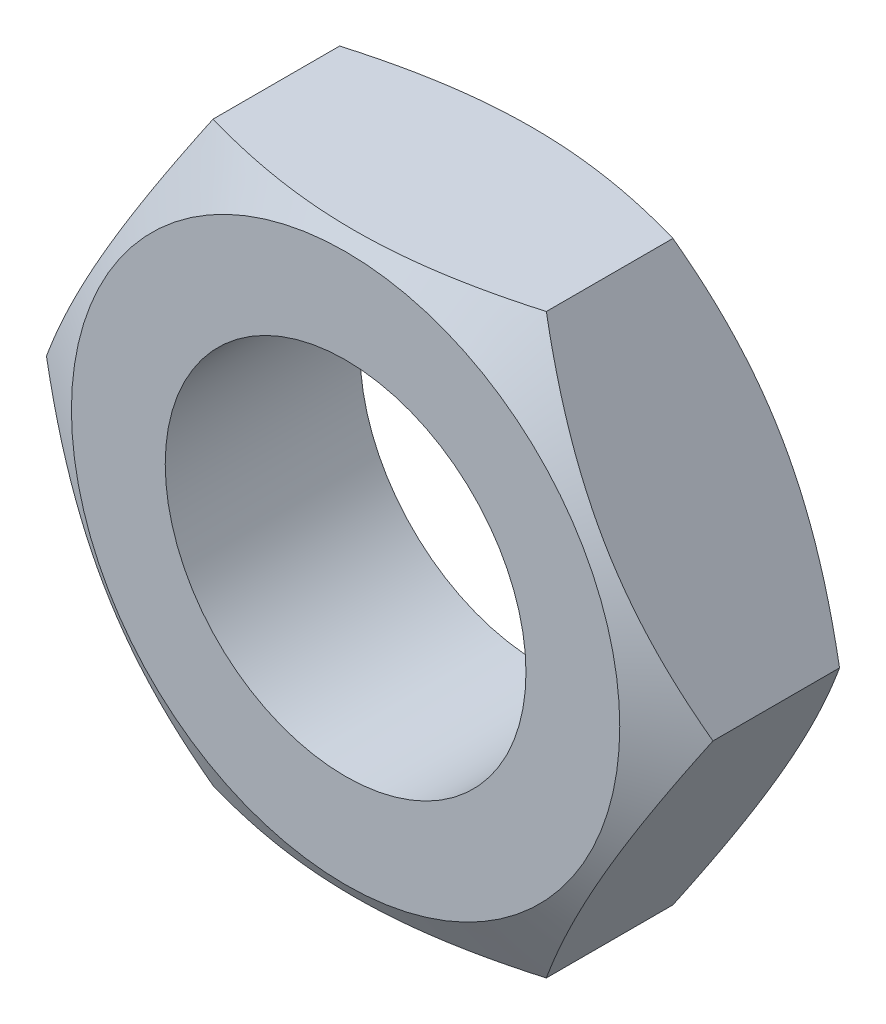
SolidWorks part; units mm, degrees
ref_plane "Plane1" through (0, 0, 0) normal (0, 0, 1) x (1, 0, 0)
ref_plane "Plane2" through (0, 0, 0) normal (0, 1, 0) x (1, 0, 0)
ref_plane "Plane3" through (0, 0, 0) normal (1, 0, 0) x (0, 0, -1)
sketch "BaseNutSke" plane through (0, 0, 0) normal (0, 0, 1) x (1, 0, 0)
  line L6 (2.3094, -4) -> (-2.3094, -4)
  line L7 (2.3094, 4) -> (-2.3094, 4)
  line L8 (2.3094, -4) -> (4.6188, 0)
  line L9 (4.6188, 0) -> (2.3094, 4)
  line L10 (-2.3094, 4) -> (-4.6188, 0)
  line L11 (-4.6188, 0) -> (-2.3094, -4)
  circle A0 centre (0, 0) radius 2.1 construction
  circle A1 centre (0, 0) radius 4.6188 construction
  circle A2 centre (0, 0) radius 2.5
  dimension "Tap_drill" = 4.2
  dimension "Diameter" = 5
  dimension "Width_flats" = 8
extrude "BaseNut" add sketch "BaseNutSke" against normal blind 2.7
cosmetic thread "ThreadCosmetic" [suppressed] parameters "Thread_major"=5
ref_plane "Plane4" through (0, 0, -1.35) normal (0, 0, -1) x (-1, 0, 0)
sketch "Sketch6" plane through (0, 0, -2.7) normal (0, 0, -1) x (-1, 0, 0)
  circle A0 centre (0, 0) radius 3.8
  dimension "D1" = 7.6
extrude "Cut-Extrude2" cut sketch "Sketch6" against normal through all draft 60 flip side to cut
mirror "Mirror1" about plane through (0, 0, -1.35) normal (0, 0, -1) of "Cut-Extrude2"
equation "\"D1@Sketch3\" = \"Width_flats@BaseNutSke\" /2"
equation "' \"Num_threads@ThdSchPat\" = \"Num_threads@ThdSchPat\" - sgn( \"Num_threads@ThdSchPat\" - 1) '---chamfered tips only---"
equation "\"D1@Sketch6\" = 0.95 * \"Width_flats@BaseNutSke\""
